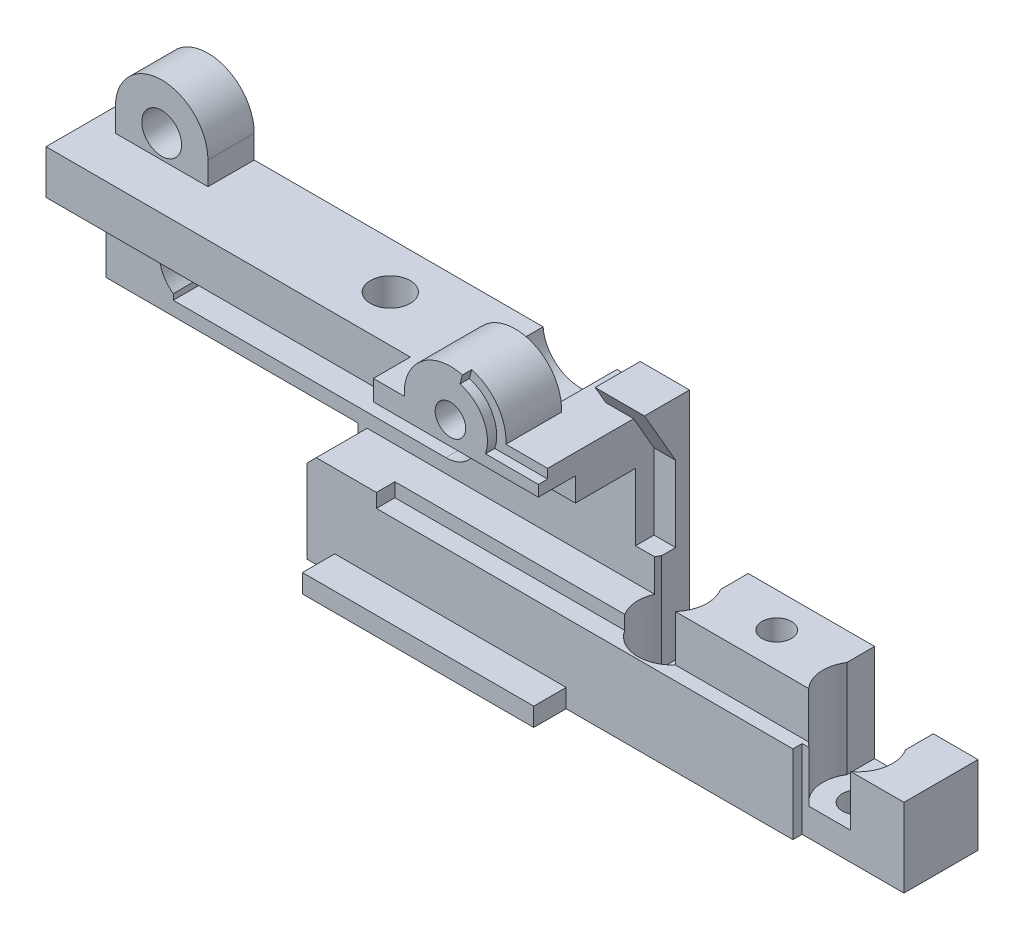
SolidWorks part; units mm, degrees
ref_plane "前视基准面" through (0, 0, 0) normal (0, 0, 1) x (1, 0, 0)
ref_plane "上视基准面" through (0, 0, 0) normal (0, 1, 0) x (1, 0, 0)
ref_plane "右视基准面" through (0, 0, 0) normal (1, 0, 0) x (0, 0, -1)
other "Configuration Table"
sketch "草图1" plane through (0, 0, 0) normal (0, 1, 0) x (1, 0, 0)
  line L0 (0, 0) -> (20, 0) construction
  line L8 (-35.5, 5) -> (28, 5)
  line L9 (-35.5, 5) -> (-35.5, -3)
  line L10 (-35.5, -3) -> (28, -3)
  line L11 (28, 5) -> (28, -3)
  circle A0 centre (0, 0) radius 1.65
  circle A1 centre (20, 0) radius 1.65
  point P5 (10, 0)
  dimension "D1" = 3.3
  dimension "D3" = 3
  dimension "D4" = 8
  dimension "D2" = 20
  dimension "D5" = 5
  dimension "D6" = 63.5
extrude "凸台-拉伸1" add sketch "草图1" along normal blind 3
sketch "草图3" plane through (0, 3, 0) normal (0, 1, 0) x (1, 0, 0)
  circle A0 centre (0, 0) radius 3.75 construction
  circle A1 centre (20, 0) radius 3.75 construction
  circle A2 centre (0, 0) radius 2.75 construction
  circle A3 centre (20, 0) radius 2.75 construction
  dimension "D1" = 7.5
  dimension "D2" = 5.5
sketch "草图4" plane through (0, 3, 0) normal (0, 1, 0) x (1, 0, 0)
  line L0 (28, -3) -> (28, 5) construction
  line L1 (-35.5, -3) -> (17, -3)
  line L2 (-35.5, -3) -> (-35.5, -4)
  line L3 (-35.5, -4) -> (17, -4)
  line L4 (17, -3) -> (17, -4)
  dimension "D1" = 4
  dimension "D2" = 11
extrude "凸台-拉伸3" add sketch "草图4" against normal up to surface (3 mm away) up to face at (-3.75, 0, -1)
sketch "草图6" plane through (0, 3, 0) normal (0, 1, 0) x (1, 0, 0)
  line L0 (28, -3) -> (28, 5) construction
  line L1 (-35.5, -4) -> (17, -4)
  line L2 (-35.5, -4) -> (-35.5, 2)
  line L3 (-35.5, 2) -> (-3.1721, 2)
  line L4 (28, -3) -> (28, 2)
  line L5 (3.1721, 2) -> (16.8279, 2)
  line L6 (23.1721, 2) -> (28, 2)
  line L7 (22.25, -3) -> (28, -3)
  line L8 (17, -3) -> (17.75, -3)
  line L9 (17, -3) -> (17, -4)
  arc A0 (-3.1721, 2) -> (3.1721, 2) centre (0, 0) ccw
  arc A1 (16.8279, 2) -> (17.75, -3) centre (20, 0) ccw
  circle A2 centre (20, 0) radius 3.75 construction
  circle A3 centre (0, 0) radius 3.75 construction
  arc A4 (22.25, -3) -> (23.1721, 2) centre (20, 0) ccw
  dimension "D1" = 6
extrude "凸台-拉伸4" add sketch "草图6" along normal blind 5.5
sketch "草图7" plane through (0, 8.5, 0) normal (0, 1, 0) x (1, 0, 0)
  line L1 (-18, -4) -> (-35.5, -4)
  line L2 (-5.5, 0) -> (-5.5, 5)
  line L3 (-5.5, 5) -> (-35.5, 5)
  line L4 (-35.5, -4) -> (-35.5, 5)
  line L5 (-35.5, 5) -> (-35.5, 2) construction
  line L7 (-3.1721, 2) -> (-35.5, 2) construction
  line L10 (-5.5, 0) -> (-18, 0)
  line L11 (-18, -4) -> (-18, 0)
  line L12 (28, 5) -> (-35.5, 5) construction
  dimension "D1" = 30
  dimension "D3" = 2
  dimension "D4" = 12.5
extrude "凸台-拉伸5" add sketch "草图7" along normal offset from surface 7 and the other way up to next up to face at (20, 3, 1.65) offset beyond the face yes
chamfer "倒角1" distance 1 angle 45 1 edges at (-35.5, 10, -0.5)
sketch "草图8" plane through (0, 10, 0) normal (0, 1, 0) x (1, 0, 0)
  line L0 (-5.5, 5) -> (-5.5, 2) construction
  line L1 (-27.5, 5) -> (-5.5, 5)
  line L2 (-27.5, 5) -> (-27.5, 1.5)
  line L3 (-27.5, 1.5) -> (-5.5, 1.5)
  line L4 (-5.5, 5) -> (-5.5, 1.5)
  line L5 (-5.5, 5) -> (-34.5, 5) construction
  line L6 (-35.5, -4) -> (-35.5, 5) construction
  dimension "D1" = 3.5
  dimension "D2" = 8
extrude "凸台-拉伸6" add sketch "草图8" along normal blind 12.5
sketch "草图10" plane through (0, 8.5, 0) normal (0, 1, 0) x (1, 0, 0)
  line L0 (2.7951, -2.5) -> (17.2049, -2.5)
  line L8 (-5.5, 2) -> (-5.5, 0)
  line L9 (-5.5, 0) -> (-18, 0)
  line L10 (-18, 0) -> (-18, -4)
  line L11 (-18, -4) -> (17, -4)
  line L12 (17, -4) -> (17, -3)
  line L13 (17, -3) -> (17.75, -3)
  line L14 (16.8279, 2) -> (3.1721, 2)
  line L15 (-3.1721, 2) -> (-5.5, 2)
  line L22 (16.8279, 2) -> (3.1721, 2)
  circle A0 centre (0, 0) radius 3.75 construction
  arc A2 (16.8279, 2) -> (17.75, -3) centre (20, 0) ccw
  arc A3 (-3.1721, 2) -> (3.1721, 2) centre (0, 0) ccw
  arc A4 (16.8279, 2) -> (17.2049, -2.5) centre (20, 0) ccw
  arc A5 (2.7951, -2.5) -> (3.1721, 2) centre (0, 0) ccw
  dimension "D2" = 4.5
  dimension "D1" = 0
extrude "凸台-拉伸7" add sketch "草图10" along normal blind 5
sketch "草图11" plane through (0, 8.5, 0) normal (0, 1, 0) x (1, 0, 0)
  line L1 (-18, -4) -> (-28, -4)
  line L2 (-18, -4) -> (-18, -2)
  line L3 (-18, -2) -> (-28, -2)
  line L4 (-28, -4) -> (-28, -2)
  dimension "D1" = 2
  dimension "D2" = 10
extrude "切除-拉伸1" cut sketch "草图11" along normal blind 5
sketch "草图12" plane through (0, 0, 2.5) normal (0, 0, 1) x (1, 0, 0)
  line L0 (17.2049, 8.5) -> (14.7049, 8.5)
  line L1 (-28, 8.5) -> (17, 8.5) construction
  line L2 (14.7049, 8.5) -> (10.5094, 13.5)
  line L3 (2.7951, 13.5) -> (17.2049, 13.5) construction
  line L4 (10.5094, 13.5) -> (17.2049, 13.5)
  line L5 (17.2049, 13.5) -> (17.2049, 8.5)
  line L6 (2.7951, 8.5) -> (17.2049, 8.5) construction
  dimension "D1" = 50
  dimension "D2" = 2.5
sketch "草图14" plane through (0, 0, -1.5) normal (0, 0, 1) x (1, 0, 0)
  line L0 (-27.5, 15) -> (-5.5, 15) construction
  line L1 (-27.5, 22.5) -> (-27.5, 10) construction
  line L3 (-27.5, 15) -> (-26, 15) construction
  line L4 (-27.5, 18.5) -> (-26, 18.5)
  line L5 (-27.5, 11.5) -> (-26, 11.5)
  line L6 (-27.5, 10) -> (-5.5, 10) construction
  line L7 (-5.5, 22.5) -> (-5.5, 10) construction
  arc A0 (-27.5, 18.5) -> (-27.5, 11.5) centre (-27.5, 15) ccw
  arc A1 (-26, 11.5) -> (-26, 18.5) centre (-26, 15) ccw
  point P6 (-26.75, 15)
  dimension "D1" = 5
  dimension "D2" = 7
  dimension "D3" = 1.5
extrude "切除-拉伸3" cut sketch "草图14" against normal through all
sketch "草图15" plane through (0, 0, -1.5) normal (0, 0, 1) x (1, 0, 0)
  line L0 (-27.5, 10) -> (-34.5, 10)
  line L1 (-34.5, 10) -> (-35.5, 9)
  line L2 (-35.5, 9) -> (-35.5, 11.5)
  line L3 (-35.5, 11.5) -> (-27.5, 11.5)
  line L4 (-27.5, 11.5) -> (-27.5, 10)
extrude "凸台-拉伸8" add sketch "草图15" against normal up to surface (3.5 mm away) up to face at (-16.8462, 10.7692, -5)
sketch "草图16" plane through (-27.5, 0, 0) normal (-1, 0, 0) x (0, 0, 1)
  line L4 (-5, 22.5) -> (-5, 18.5)
  line L5 (-5, 18.5) -> (-1.5, 18.5)
  line L6 (-1.5, 18.5) -> (-1.5, 22.5)
  line L7 (-1.5, 22.5) -> (-5, 22.5)
  line L8 (-5, 22.5) -> (-5, 18.5)
  line L9 (-5, 18.5) -> (-1.5, 18.5)
  line L10 (-1.5, 18.5) -> (-1.5, 22.5)
  line L11 (-1.5, 22.5) -> (-5, 22.5)
  dimension "D1" = 0
extrude "凸台-拉伸9" add sketch "草图16" along normal up to surface (8 mm away) up to face at (-35.5, 6.8333, -0.8333)
sketch "草图2" plane through (0, 3, 0) normal (0, 1, 0) x (1, 0, 0)
  line L1 (5, -3) -> (15, -3)
  line L2 (5, -3) -> (5, -1)
  line L3 (5, -1) -> (15, -1)
  line L4 (15, -3) -> (15, -1)
  line L5 (17.75, -3) -> (22.25, -3) construction
  circle A2 centre (0, 0) radius 3.75 construction
  circle A3 centre (20, 0) radius 3.75 construction
  dimension "D4" = 7.5
  dimension "D1" = 5
  dimension "D2" = 2
  dimension "D3" = 10
extrude "凸台-拉伸2" add sketch "草图2" along normal blind 3
sketch "草图17" plane through (0, 0, -5) normal (0, 0, -1) x (-1, 0, 0)
  line L0 (5.5, 3) -> (5.5, 22.5) construction
  line L1 (5.5, 20.75) -> (35.5, 20.75)
  line L2 (5.5, 20.75) -> (5.5, 25.5)
  line L3 (5.5, 25.5) -> (35.5, 25.5)
  line L4 (35.5, 20.75) -> (35.5, 25.5)
  line L5 (35.5, 18.5) -> (35.5, 22.5) construction
  line L6 (5.5, 22.5) -> (35.5, 22.5) construction
  dimension "D1" = 4.75
  dimension "D2" = 1.75
extrude "凸台-拉伸10" add sketch "草图17" against normal blind 10
sketch "草图18" plane through (0, 8.5, 0) normal (0, 1, 0) x (1, 0, 0)
  line L0 (-5.5, 2) -> (-5.5, -2)
  line L1 (-5.5, -5) -> (-5.5, 5) construction
  line L2 (-3.1721, 2) -> (-5.5, 2) construction
  line L3 (-5.5, -2) -> (-3.1721, -2)
  line L4 (-5.5, 2) -> (-3.1721, 2)
  circle A0 centre (0, 0) radius 3.75 construction
  arc A1 (-3.1721, 2) -> (2.7951, -2.5) centre (0, 0) ccw construction
  arc A2 (-3.1721, 2) -> (-3.1721, -2) centre (0, 0) ccw
  dimension "D1" = 4
extrude "凸台-拉伸11" add sketch "草图18" along normal up to surface (17 mm away) up to face at (-20.5, 25.5, 0)
sketch "草图19" plane through (0, 3, 0) normal (0, 1, 0) x (1, 0, 0)
  line L0 (28, 5) -> (-5.5, 5) construction
  line L1 (-3.1721, 2) -> (-5.5, 2)
  line L2 (-3.1721, 2) -> (-3.1721, 5)
  line L3 (-3.1721, 5) -> (-5.5, 5)
  line L4 (-5.5, 2) -> (-5.5, 5)
  line L5 (3.1721, 2) -> (16.8279, 2)
  line L6 (3.1721, 2) -> (3.1721, 5)
  line L7 (3.1721, 5) -> (16.8279, 5)
  line L8 (16.8279, 2) -> (16.8279, 5)
  line L10 (23.1721, 2) -> (28, 2)
  line L11 (23.1721, 2) -> (23.1721, 5)
  line L12 (23.1721, 5) -> (28, 5)
  line L13 (28, 2) -> (28, 5)
extrude "凸台-拉伸12" add sketch "草图19" along normal up to surface (10.5 mm away) up to face at (10, 13.5, 0.2816)
sketch "草图21" plane through (0, 0, -5) normal (0, 0, -1) x (-1, 0, 0)
  line L0 (35.5, 18.5) -> (35.5, 25.5) construction
  line L1 (35.5, 25.5) -> (5.5, 25.5) construction
  circle A0 centre (15, 25.8) radius 1.65
  dimension "D2" = 0.3
  dimension "D3" = 3.3
  dimension "D1" = 20.5
extrude "切除-拉伸4" cut sketch "草图21" against normal through all
sketch "草图22" plane through (0, 0, 5) normal (0, 0, 1) x (1, 0, 0)
  line L0 (-35.5, 23.3) -> (-3.1721, 23.3) construction
  line L2 (-3.1721, 25.5) -> (-3.1721, 8.5) construction
  line L3 (-35.5, 20.75) -> (-35.5, 25.5) construction
  line L4 (-19.3361, 23.3) -> (-10.6699, 23.3)
  arc A0 (-16.6225, 25.5) -> (-13.3775, 25.5) centre (-15, 25.8) ccw construction
  circle A1 centre (-15, 25.8) radius 1.65
  arc A2 (-10.6699, 23.3) -> (-19.3301, 23.3) centre (-15, 25.8) ccw
  arc M4 (-13.3775, 25.5) -> (-16.6225, 25.5) centre (-15, 25.8) cw
  line M5 (-16.6225, 25.5) -> (-35.5, 25.5)
  line M9 (-5.5, 25.5) -> (-13.3775, 25.5)
  dimension "D1" = 2.5
  dimension "D2" = 10
extrude "凸台-拉伸13" add sketch "草图22" along normal blind 4 and the other way blind 3 contours A2 L4 M5 M9 M4 | A2 A1 M9 M5
sketch "草图23" plane through (0, 0, 2) normal (0, 0, -1) x (-1, 0, 0)
  circle A0 centre (15, 25.8) radius 4
  dimension "D1" = 8
extrude "切除-拉伸5" cut sketch "草图23" along normal through all
sketch "草图24" plane through (0, 0, 5) normal (0, 0, 1) x (1, 0, 0)
  line L0 (-35.5, 25.5) -> (-19.991, 25.5) construction
  line L1 (-10.6699, 23.3) -> (-5.5, 23.3)
  line L2 (-10.6699, 23.3) -> (-10.6699, 25.5)
  line L3 (-10.6699, 25.5) -> (-5.5, 25.5)
  line L4 (-5.5, 23.3) -> (-5.5, 25.5)
  line L5 (-19.3301, 23.3) -> (-23.3301, 23.3)
  line L6 (-19.3301, 23.3) -> (-19.3301, 25.5)
  line L7 (-19.3301, 25.5) -> (-23.3301, 25.5)
  line L8 (-23.3301, 23.3) -> (-23.3301, 25.5)
  dimension "D1" = 4
extrude "凸台-拉伸14" add sketch "草图24" along normal up to surface (4 mm away) up to face at (-15, 27.05, 9)
sketch "草图25" plane through (0, 0, 9) normal (0, 0, 1) x (1, 0, 0)
  line L1 (-13.9647, 29.6637) -> (-13.7059, 30.6296)
  line L2 (-5.5, 24.5) -> (-11.2171, 24.5)
  line L3 (-5.5, 24.5) -> (-11.2171, 24.5)
  line L4 (-5.5, 25.5) -> (-5.5, 20.75) construction
  line L5 (-5.5, 25.5) -> (-10.009, 25.5) construction
  line L6 (-5.5, 25.5) -> (-5.5, 24.5)
  line L7 (-5.5, 25.5) -> (-10.009, 25.5)
  arc A2 (-10.009, 25.5) -> (-19.991, 25.5) centre (-15, 25.8) ccw construction
  arc A3 (-11.2171, 24.5) -> (-18.9928, 25.56) centre (-15, 25.8) ccw
  arc A4 (-11.2171, 24.5) -> (-13.9647, 29.6637) centre (-15, 25.8) ccw
  arc A5 (-10.009, 25.5) -> (-13.7059, 30.6296) centre (-15, 25.8) ccw
  dimension "D2" = 75
  dimension "D1" = 1
extrude "切除-拉伸6" cut sketch "草图25" against normal blind 1
sketch "草图26" plane through (0, 25.5, 0) normal (0, 1, 0) x (1, 0, 0)
  line L0 (-35.5, 0) -> (-30.5, 0) construction
  line L1 (-35.5, -5) -> (-35.5, 5) construction
  circle A0 centre (-30.5, 0) radius 2.15
  dimension "D1" = 4.3
  dimension "D2" = 5
extrude "切除-拉伸7" cut sketch "草图26" against normal up to surface (4.75 mm away) up to face at (-17.5, 20.75, 1.8)
sketch "草图27" plane through (0, 0, -5) normal (0, 0, -1) x (-1, 0, 0)
  line L0 (35.5, 11.5) -> (35.5, 0) construction
  line L1 (35.5, 10) -> (62.7, 10)
  line L2 (35.5, 10) -> (35.5, 11.5)
  line L3 (35.5, 25.5) -> (62.7, 25.5)
  line L4 (62.7, 10) -> (62.7, 25.5)
  line L5 (35.5, 25.5) -> (18.9887, 25.5) construction
  line L6 (35.5, 18.5) -> (35.5, 25.5) construction
  line L7 (35.5, 11.5) -> (26, 11.5) construction
  line L8 (26, 15) -> (53.45, 15) construction
  line L9 (35.5, 18.5) -> (53.45, 18.5)
  line L10 (35.5, 11.5) -> (53.45, 11.5)
  line L12 (35.5, 18.5) -> (35.5, 25.5)
  line L13 (26, 18.5) -> (35.5, 18.5) construction
  arc A1 (53.45, 11.5) -> (53.45, 18.5) centre (53.45, 15) ccw
  point P15 (39.725, 15)
  dimension "D1" = 1.5
  dimension "D2" = 27.45
  dimension "D3" = 9.25
extrude "凸台-拉伸15" add sketch "草图27" against normal up to surface (3.5 mm away) up to face at (-27, 15.6364, -1.5)
sketch "草图28" plane through (-35.5, 0, 0) normal (-1, 0, 0) x (0, 0, 1)
  line L4 (-1.5, 25.5) -> (-1.5, 20.75)
  line L5 (-1.5, 20.75) -> (5, 20.75)
  line L6 (5, 20.75) -> (5, 25.5)
  line L7 (5, 25.5) -> (-1.5, 25.5)
  line L8 (-1.5, 25.5) -> (-1.5, 20.75)
  line L9 (-1.5, 20.75) -> (5, 20.75)
  line L10 (5, 20.75) -> (5, 25.5)
  line L11 (5, 25.5) -> (-1.5, 25.5)
  dimension "D1" = 0
extrude "凸台-拉伸16" add sketch "草图28" along normal up to surface (27.2 mm away) up to face at (-62.7, 17.75, -3.25)
sketch "草图29" plane through (0, 0, -5) normal (0, 0, -1) x (-1, 0, 0)
  line L0 (62.7, 25.5) -> (18.9887, 25.5) construction
  line L1 (62.7, 10) -> (62.7, 25.5) construction
  line L2 (60.2, 28) -> (60.2, 25.5)
  line L3 (60.2, 25.5) -> (50.2, 25.5)
  line L4 (50.2, 25.5) -> (50.2, 28)
  circle A0 centre (55.2, 28) radius 2.15
  arc A1 (60.2, 28) -> (50.2, 28) centre (55.2, 28) ccw
  dimension "D1" = 4.3
  dimension "D3" = 7.5
  dimension "D4" = 10
  dimension "D2" = 2.5
extrude "凸台-拉伸17" add sketch "草图29" against normal blind 5
sketch "草图30" plane through (0, 13.5, 0) normal (0, 1, 0) x (1, 0, 0)
  line L0 (10, 5) -> (10, -2.5) construction
  line L1 (16.8279, 5) -> (3.1721, 5) construction
  line L2 (2.7951, -2.5) -> (17.2049, -2.5) construction
  circle A0 centre (10, 1.25) radius 1.6
  dimension "D1" = 3.2
extrude "切除-拉伸8" cut sketch "草图30" against normal blind 5
sketch "草图31" plane through (0, 0, 4) normal (0, 0, 1) x (1, 0, 0)
  line L1 (-35.5, 0) -> (-7.5, 0)
  line L2 (-35.5, 0) -> (-35.5, 2)
  line L3 (-35.5, 2) -> (-7.5, 2)
  line L4 (-7.5, 0) -> (-7.5, 2)
  dimension "D1" = 2
  dimension "D2" = 28
extrude "凸台-拉伸18" add sketch "草图31" along normal blind 3.5
sketch "草图32" plane through (-5.5, 0, 0) normal (-1, 0, 0) x (0, 0, 1)
  line L6 (-1.5, 10) -> (0, 10)
  line L7 (0, 10) -> (0, 8.5)
  line L8 (0, 8.5) -> (2, 8.5)
  line L9 (2, 8.5) -> (2, 20.75)
  line L10 (2, 20.75) -> (-1.5, 20.75)
  line L11 (-1.5, 20.75) -> (-1.5, 10)
  line L12 (-1.5, 10) -> (0, 10)
  line L13 (0, 10) -> (0, 8.5)
  line L14 (0, 8.5) -> (2, 8.5)
  line L15 (2, 8.5) -> (2, 20.75)
  line L16 (2, 20.75) -> (-1.5, 20.75)
  line L17 (-1.5, 20.75) -> (-1.5, 10)
  dimension "D1" = 0
extrude "切除-拉伸9" cut sketch "草图32" against normal blind 2.5
sketch "草图33" plane through (0, 8.5, 0) normal (0, 1, 0) x (1, 0, 0)
  line L1 (-18, 0) -> (-3.75, 0)
  line L2 (-18, 0) -> (-18, -2)
  line L3 (-18, -2) -> (-3.1721, -2)
  arc A0 (-3.75, 0) -> (2.7951, -2.5) centre (0, 0) ccw construction
  arc A1 (-3.75, 0) -> (-3.1721, -2) centre (0, 0) ccw
extrude "凸台-拉伸19" add sketch "草图33" along normal up to surface (1.5 mm away) up to face at (-21.033, 10, 1.123)
sketch "草图34" plane through (-5.5, 0, 0) normal (1, 0, 0) x (0, 0, -1)
  line L0 (2, 25.5) -> (2, 13.5) construction
  line L1 (-2, 25.5) -> (2, 25.5)
  line L2 (-2, 25.5) -> (-2, 13.5)
  line L3 (-2, 13.5) -> (2, 13.5)
  line L4 (2, 25.5) -> (2, 13.5)
  line L5 (-2, 25.5) -> (2, 13.5) construction
  line L6 (-2, 13.5) -> (2, 25.5) construction
  line L7 (5, 13.5) -> (2, 13.5) construction
  point P4 (0, 19.5)
extrude "切除-拉伸10" cut sketch "草图34" along normal through all
sketch "草图35" plane through (0, 13.5, 0) normal (0, 1, 0) x (1, 0, 0)
  line L4 (28, 5) -> (23.1721, 5)
  line L5 (23.1721, 5) -> (23.1721, 2)
  line L6 (23.1721, 2) -> (28, 2)
  line L7 (28, 2) -> (28, 5)
  line L8 (28, 5) -> (23.1721, 5)
  line L9 (23.1721, 5) -> (23.1721, 2)
  line L10 (23.1721, 2) -> (28, 2)
  line L11 (28, 2) -> (28, 5)
  dimension "D1" = 0
extrude "切除-拉伸11" cut sketch "草图35" against normal up to surface (5 mm away) up to face at (25.5997, 8.5, 0.545)
sketch "草图36" plane through (0, 13.5, 0) normal (0, 1, 0) x (1, 0, 0)
  line L1 (-3.1721, 2) -> (-3.1721, 5) construction
  line L2 (-5.5, 5) -> (-3.1721, 5)
  line L3 (-5.5, 5) -> (-5.5, 3.5)
  line L4 (-5.5, 3.5) -> (-3.1721, 3.5)
  line L5 (-3.1721, 5) -> (-3.1721, 3.5)
  dimension "D1" = 1.5
extrude "凸台-拉伸20" add sketch "草图36" along normal offset from surface (14 mm away) 2 up to face at (-39.235, 25.5, 1) offset beyond the face yes
sketch "草图37" plane through (0, 25.5, 0) normal (0, 1, 0) x (1, 0, 0)
  line L0 (-11.0113, 5) -> (-5.5, 5) construction
  line L1 (-5.5, 3.5) -> (-8.5, 3.5)
  line L2 (-5.5, 3.5) -> (-5.5, 5)
  line L3 (-5.5, 5) -> (-8.5, 5)
  line L4 (-8.5, 3.5) -> (-8.5, 5)
  dimension "D1" = 3
extrude "凸台-拉伸21" add sketch "草图37" along normal up to surface (2 mm away) up to face at (-4.3361, 27.5, -4.25)
sketch "草图38" plane through (0, 2, 0) normal (0, 1, 0) x (1, 0, 0)
  line L0 (-7.5, -7.5) -> (-35.5, -7.5) construction
  line L1 (-35.5, -4) -> (-32.5, -4)
  line L2 (-35.5, -4) -> (-35.5, -7.5)
  line L3 (-35.5, -7.5) -> (-32.5, -7.5)
  line L4 (-32.5, -4) -> (-32.5, -7.5)
  dimension "D1" = 3
extrude "切除-拉伸12" cut sketch "草图38" against normal blind 10
sketch "草图39" plane through (0, 0, -5) normal (0, 0, -1) x (-1, 0, 0)
  line L0 (53.45, 11.5) -> (26, 11.5) construction
  line L1 (53.45, 18.5) -> (55.45, 18.5)
  line L2 (53.45, 18.5) -> (53.45, 11.5)
  line L3 (53.45, 11.5) -> (55.45, 11.5)
  line L4 (55.45, 18.5) -> (55.45, 11.5)
  dimension "D1" = 2
extrude "切除-拉伸13" cut sketch "草图39" against normal up to surface (3.5 mm away) up to face at (-39.725, 15, -1.5)
sketch "草图40" plane through (-5.5, 0, 0) normal (1, 0, 0) x (0, 0, -1)
  line L0 (3.5, 26) -> (1, 26) construction
  line L1 (3.5, 27.5) -> (3.5, 13.5) construction
  line L2 (0, 25.5) -> (5, 25.5) construction
  line L3 (3.5, 27.5) -> (0.134, 27.5)
  line L4 (0.134, 27.5) -> (3.5, 21.6699)
  line L5 (3.5, 25.5) -> (3.5, 13.5) construction
  line L6 (3.5, 21.6699) -> (3.5, 27.5)
  dimension "D1" = 2.5
  dimension "D2" = 0.5
  dimension "D3" = 30
extrude "凸台-拉伸22" add sketch "草图40" along normal up to surface and the other way up to surface up to face at (-3.1721, 14.6667, -3.5) other way up to face at (-8.5, 26.5, -4.25)
